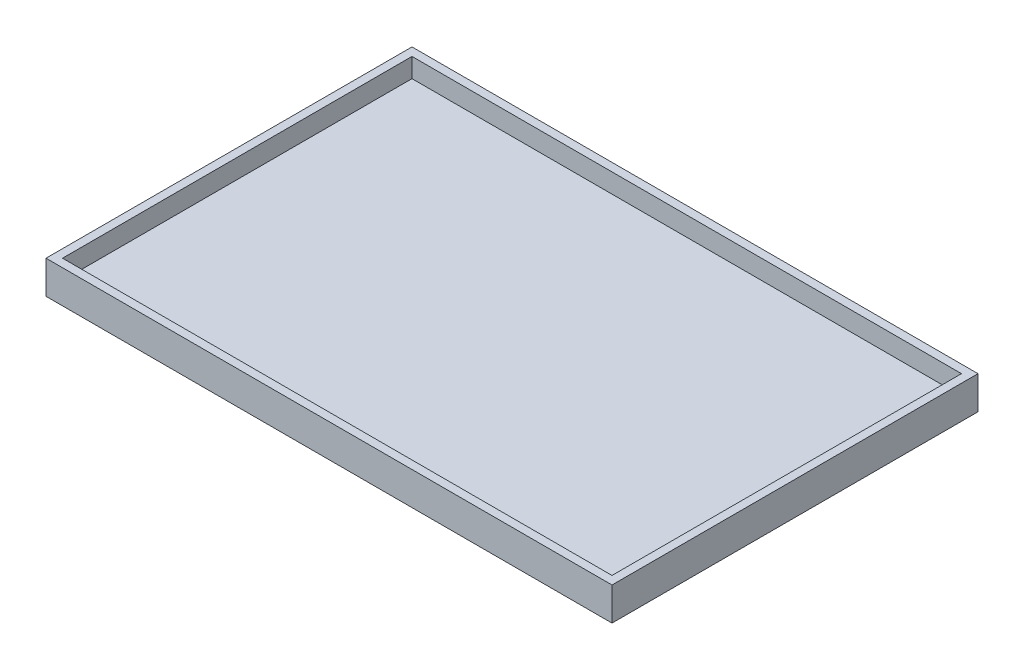
SolidWorks part; units mm, degrees
ref_plane "Front Plane" through (0, 0, 0) normal (0, 0, 1) x (1, 0, 0)
ref_plane "Top Plane" through (0, 0, 0) normal (0, 1, 0) x (1, 0, 0)
ref_plane "Right Plane" through (0, 0, 0) normal (1, 0, 0) x (0, 0, -1)
sketch "Sketch1" plane through (0, 0, 0) normal (0, 1, 0) x (1, 0, 0)
  line L1 (-49.405, 31.24) -> (49.405, 31.24)
  line L2 (-49.405, 31.24) -> (-49.405, -31.24)
  line L3 (-49.405, -31.24) -> (49.405, -31.24)
  line L4 (49.405, 31.24) -> (49.405, -31.24)
  line L5 (-49.405, 31.24) -> (49.405, -31.24) construction
  line L6 (-49.405, -31.24) -> (49.405, 31.24) construction
  point P0 (0, 0)
  dimension "D1" = 98.81
  dimension "D2" = 62.48
extrude "Boss-Extrude1" add sketch "Sketch1" along normal blind 1.5
sketch "Sketch2" plane through (0, 1.5, 0) normal (0, 1, 0) x (1, 0, 0)
  line L0 (-49.905, 31.74) -> (-49.905, -31.74)
  line L1 (-49.905, -31.74) -> (49.905, -31.74)
  line L2 (49.905, -31.74) -> (49.905, 31.74)
  line L3 (49.905, 31.74) -> (-49.905, 31.74)
  line L4 (49.405, -31.24) -> (49.405, 31.24)
  line L5 (49.405, 31.24) -> (-49.405, 31.24)
  line L6 (-49.405, 31.24) -> (-49.405, -31.24)
  line L7 (-49.405, -31.24) -> (49.405, -31.24)
  line L8 (49.405, -31.24) -> (49.405, 31.24)
  line L9 (49.405, 31.24) -> (-49.405, 31.24)
  line L10 (-49.405, 31.24) -> (-49.405, -31.24)
  line L11 (-49.405, -31.24) -> (49.405, -31.24)
  line L12 (51.405, 33.24) -> (-51.405, 33.24)
  line L13 (-51.405, 33.24) -> (-51.405, -33.24)
  line L14 (-51.405, -33.24) -> (51.405, -33.24)
  line L15 (51.405, -33.24) -> (51.405, 33.24)
  dimension "D1" = 0
  dimension "D2" = 0.5
  dimension "D3" = 1.5
extrude "Boss-Extrude2" add sketch "Sketch2" along normal blind 3 and the other way blind 3 separate body contours L14 L15 L12 L13 L3 L2 L1 L0
